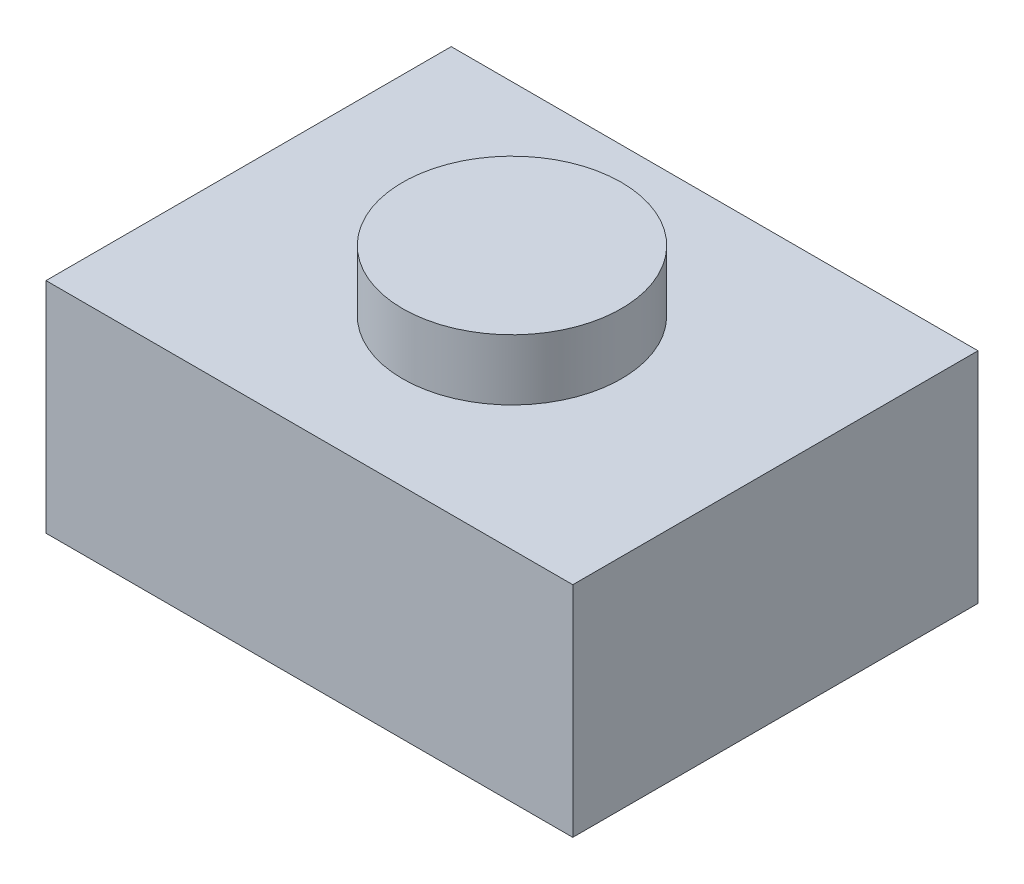
SolidWorks part; units mm, degrees
ref_plane "Front Plane" through (0, 0, 0) normal (0, 0, 1) x (1, 0, 0)
ref_plane "Top Plane" through (0, 0, 0) normal (0, 1, 0) x (1, 0, 0)
ref_plane "Right Plane" through (0, 0, 0) normal (1, 0, 0) x (0, 0, -1)
sketch "Sketch1" plane through (0, 0, 0) normal (0, 1, 0) x (1, 0, 0)
  line L1 (0, 0) -> (3.302, 0)
  line L2 (0, 0) -> (0, 2.54)
  line L3 (0, 2.54) -> (3.302, 2.54)
  line L4 (3.302, 0) -> (3.302, 2.54)
  dimension "D1" = 3.302
  dimension "D2" = 2.54
extrude "Boss-Extrude1" add sketch "Sketch1" along normal blind 1.3716
sketch "Sketch2" plane through (0, 1.3716, 0) normal (0, 1, 0) x (1, 0, 0)
  line L0 (0, 2.54) -> (3.302, 0) construction
  line L1 (3.302, 0) -> (0, 0) construction
  line L2 (0, 0) -> (3.302, 2.54) construction
  circle A0 centre (1.651, 1.27) radius 0.6858
  dimension "D1" = 1.3716
extrude "Boss-Extrude2" add sketch "Sketch2" along normal blind 0.381
